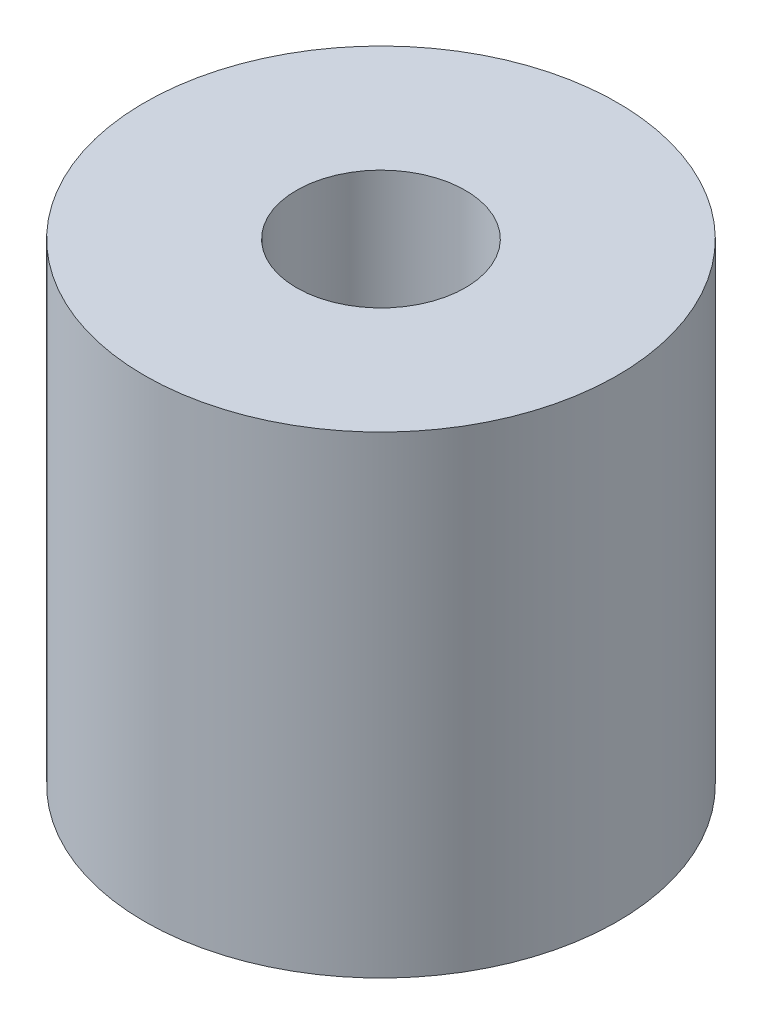
SolidWorks part; units mm, degrees
ref_plane "Front Plane" through (0, 0, 0) normal (0, 0, 1) x (1, 0, 0)
ref_plane "Top Plane" through (0, 0, 0) normal (0, 1, 0) x (1, 0, 0)
ref_plane "Right Plane" through (0, 0, 0) normal (1, 0, 0) x (0, 0, -1)
sketch "Sketch1" plane through (0, 0, 0) normal (0, 1, 0) x (1, 0, 0)
  circle A0 centre (0, 0) radius 2.5
  circle A1 centre (0, 0) radius 7
extrude "Boss-Extrude1" add sketch "Sketch1" along normal blind 14
